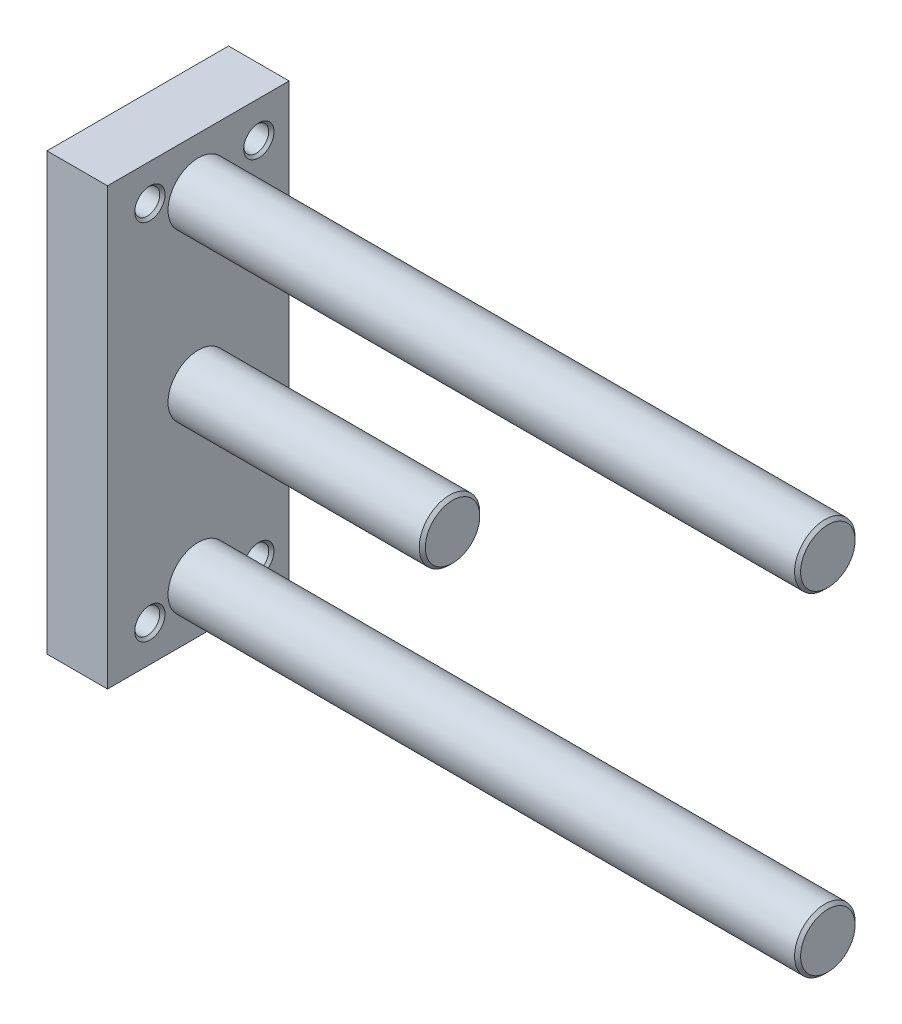
SolidWorks part; units mm, degrees
ref_plane "Front" through (0, 0, 0) normal (0, 0, 1) x (1, 0, 0)
ref_plane "Top" through (0, 0, 0) normal (0, 1, 0) x (1, 0, 0)
ref_plane "Right" through (0, 0, 0) normal (1, 0, 0) x (0, 0, -1)
ref_plane "Plane1" through (0, 0, 0) normal (1, 0, 0) x (0, 0, -1)
sketch "Sketch1" plane through (0, 0, 0) normal (1, 0, 0) x (0, 0, -1)
  line L0 (-15, -36) -> (15, -36)
  line L1 (15, -36) -> (15, 36)
  line L2 (15, 36) -> (-15, 36)
  line L3 (-15, 36) -> (-15, -36)
extrude "Boss-Extrude1" add sketch "Sketch1" along normal blind 10
ref_plane "Plane2" through (0, 30, 0) normal (0, 1, 0) x (-1, 0, 0)
sketch "Sketch2" plane through (0, 30, 0) normal (0, 1, 0) x (-1, 0, 0)
  line L0 (0, -10) -> (0, -12.5)
  line L1 (0, -12.5) -> (-0.433, -12.067)
  line L2 (-0.433, -12.067) -> (-9.567, -12.067)
  line L3 (-9.567, -12.067) -> (-10, -12.5)
  line L4 (-10, -12.5) -> (-10, -10)
  line L5 (-10, -10) -> (0, -10)
  line L6 (-10, -10) -> (0, -10) construction
revolve "Cut-Revolve1" cut sketch "Sketch2" angle 360 about L6
cosmetic thread "Cosmetic Thread1" parameters "D1"=9.134, "D2"=5
ref_plane "Plane3" through (0, 30, 0) normal (0, 1, 0) x (-1, 0, 0)
sketch "Sketch3" plane through (0, 30, 0) normal (0, 1, 0) x (-1, 0, 0)
  line L0 (0, 8) -> (0, 5.5)
  line L1 (0, 5.5) -> (-0.433, 5.933)
  line L2 (-0.433, 5.933) -> (-9.567, 5.933)
  line L3 (-9.567, 5.933) -> (-10, 5.5)
  line L4 (-10, 5.5) -> (-10, 8)
  line L5 (-10, 8) -> (0, 8)
  line L6 (-10, 8) -> (0, 8) construction
revolve "Cut-Revolve2" cut sketch "Sketch3" angle 360 about L6
ref_plane "Plane4" through (0, -30, 0) normal (0, 1, 0) x (-1, 0, 0)
sketch "Sketch4" plane through (0, -30, 0) normal (0, 1, 0) x (-1, 0, 0)
  line L0 (0, 8) -> (0, 5.5)
  line L1 (0, 5.5) -> (-0.433, 5.933)
  line L2 (-0.433, 5.933) -> (-9.567, 5.933)
  line L3 (-9.567, 5.933) -> (-10, 5.5)
  line L4 (-10, 5.5) -> (-10, 8)
  line L5 (-10, 8) -> (0, 8)
  line L6 (-10, 8) -> (0, 8) construction
revolve "Cut-Revolve3" cut sketch "Sketch4" angle 360 about L6
ref_plane "Plane5" through (0, -30, 0) normal (0, 1, 0) x (-1, 0, 0)
sketch "Sketch5" plane through (0, -30, 0) normal (0, 1, 0) x (-1, 0, 0)
  line L0 (0, -10) -> (0, -12.5)
  line L1 (0, -12.5) -> (-0.433, -12.067)
  line L2 (-0.433, -12.067) -> (-9.567, -12.067)
  line L3 (-9.567, -12.067) -> (-10, -12.5)
  line L4 (-10, -12.5) -> (-10, -10)
  line L5 (-10, -10) -> (0, -10)
  line L6 (-10, -10) -> (0, -10) construction
revolve "Cut-Revolve4" cut sketch "Sketch5" angle 360 about L6
ref_plane "Plane6" through (0, 27.5, 0) normal (0, 1, 0) x (-1, 0, 0)
sketch "Sketch6" plane through (0, 27.5, 0) normal (0, 1, 0) x (-1, 0, 0)
  line L0 (0, 0) -> (0, -3.8)
  line L1 (0, -3.8) -> (-5.5556, -3.8)
  line L2 (-5.5556, -3.8) -> (-5.5556, -3.5)
  line L3 (-5.5556, -3.5) -> (-2.0556, -3.5)
  line L4 (-2.0556, -3.5) -> (-1.5556, -3)
  line L5 (-1.5556, -3) -> (-1.5556, -1.5)
  line L6 (-1.5556, -1.5) -> (-4.1556, -1.5)
  line L7 (-4.1556, -1.5) -> (-5.0216, 0)
  line L8 (-5.0216, 0) -> (0, 0)
  line L9 (-5.0216, 0) -> (0, 0) construction
revolve "Cut-Revolve5" cut sketch "Sketch6" angle 360 about L9
ref_plane "Plane7" through (0, 0, 0) normal (0, 1, 0) x (-1, 0, 0)
sketch "Sketch7" plane through (0, 0, 0) normal (0, 1, 0) x (-1, 0, 0)
  line L0 (0, 0) -> (0, -3.8)
  line L1 (0, -3.8) -> (-5.5556, -3.8)
  line L2 (-5.5556, -3.8) -> (-5.5556, -3.5)
  line L3 (-5.5556, -3.5) -> (-2.0556, -3.5)
  line L4 (-2.0556, -3.5) -> (-1.5556, -3)
  line L5 (-1.5556, -3) -> (-1.5556, -1.5)
  line L6 (-1.5556, -1.5) -> (-4.1556, -1.5)
  line L7 (-4.1556, -1.5) -> (-5.0216, 0)
  line L8 (-5.0216, 0) -> (0, 0)
  line L9 (-5.0216, 0) -> (0, 0) construction
revolve "Cut-Revolve6" cut sketch "Sketch7" angle 360 about L9
ref_plane "Plane8" through (0, -27.5, 0) normal (0, 1, 0) x (-1, 0, 0)
sketch "Sketch8" plane through (0, -27.5, 0) normal (0, 1, 0) x (-1, 0, 0)
  line L0 (0, 0) -> (0, -3.8)
  line L1 (0, -3.8) -> (-5.5556, -3.8)
  line L2 (-5.5556, -3.8) -> (-5.5556, -3.5)
  line L3 (-5.5556, -3.5) -> (-2.0556, -3.5)
  line L4 (-2.0556, -3.5) -> (-1.5556, -3)
  line L5 (-1.5556, -3) -> (-1.5556, -1.5)
  line L6 (-1.5556, -1.5) -> (-4.1556, -1.5)
  line L7 (-4.1556, -1.5) -> (-5.0216, 0)
  line L8 (-5.0216, 0) -> (0, 0)
  line L9 (-5.0216, 0) -> (0, 0) construction
revolve "Cut-Revolve7" cut sketch "Sketch8" angle 360 about L9
ref_plane "Plane9" through (0, 0, 0) normal (0, 1, 0) x (-1, 0, 0)
sketch "Sketch9" plane through (0, 0, 0) normal (0, 1, 0) x (-1, 0, 0)
  line L0 (-10, 0) -> (-10, -5)
  line L1 (-10, -5) -> (-51.5, -5)
  line L2 (-51.5, -5) -> (-52, -4.5)
  line L3 (-52, -4.5) -> (-52, 0)
  line L4 (-52, 0) -> (-10, 0)
  line L5 (-52, 0) -> (-10, 0) construction
revolve "Revolve1" add sketch "Sketch9" angle 360 about L5
ref_plane "Plane10" through (0, -27.5, 0) normal (0, 1, 0) x (-1, 0, 0)
sketch "Sketch10" plane through (0, -27.5, 0) normal (0, 1, 0) x (-1, 0, 0)
  line L0 (-10, 0) -> (-10, -5)
  line L1 (-10, -5) -> (-113.5, -5)
  line L2 (-113.5, -5) -> (-114, -4.5)
  line L3 (-114, -4.5) -> (-114, 0)
  line L4 (-114, 0) -> (-10, 0)
  line L5 (-114, 0) -> (-10, 0) construction
revolve "Revolve2" add sketch "Sketch10" angle 360 about L5
ref_plane "Plane11" through (0, 27.5, 0) normal (0, 1, 0) x (-1, 0, 0)
sketch "Sketch11" plane through (0, 27.5, 0) normal (0, 1, 0) x (-1, 0, 0)
  line L0 (-10, 0) -> (-10, -5)
  line L1 (-10, -5) -> (-113.5, -5)
  line L2 (-113.5, -5) -> (-114, -4.5)
  line L3 (-114, -4.5) -> (-114, 0)
  line L4 (-114, 0) -> (-10, 0)
  line L5 (-114, 0) -> (-10, 0) construction
revolve "Revolve3" add sketch "Sketch11" angle 360 about L5
